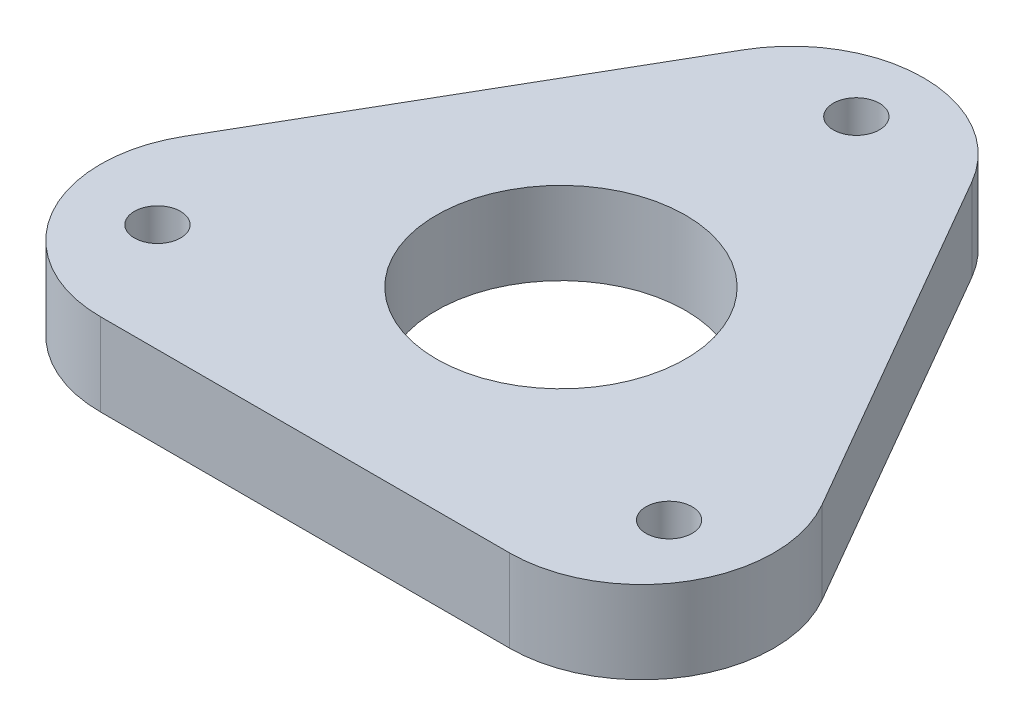
SolidWorks part; units mm, degrees
material "ASTM A36 Steel"
ref_plane "Front Plane" through (0, 0, 0) normal (0, 0, 1) x (1, 0, 0)
ref_plane "Top Plane" through (0, 0, 0) normal (0, 1, 0) x (1, 0, 0)
ref_plane "Right Plane" through (0, 0, 0) normal (1, 0, 0) x (0, 0, -1)
sketch "Sketch1" plane through (0, 0, 0) normal (0, 1, 0) x (1, 0, 0)
  line L0 (66.646, 85.1049) -> (128.644, -22.2787)
  line L1 (94.0029, -82.2787) -> (-29.993, -82.2787)
  line L2 (-64.634, -22.2787) -> (-2.636, 85.1049)
  arc A0 (66.646, 85.1049) -> (-2.636, 85.1049) centre (32.005, 65.1049) ccw
  arc A1 (-29.993, -82.2787) -> (-64.634, -22.2787) centre (-29.993, -42.2787) cw
  arc A2 (128.644, -22.2787) -> (94.0029, -82.2787) centre (94.0029, -42.2787) cw
  point P7 (-99.275, -82.2787)
  point P10 (163.285, -82.2787)
  dimension "D2" = 40
  dimension "D1" = 262.56
extrude "Boss-Extrude1" add sketch "Sketch1" along normal blind 25
sketch "Sketch2" plane through (0, 25, 0) normal (0, 1, 0) x (1, 0, 0)
  circle A0 centre (32.005, -4.7521) radius 37.75
  dimension "D1" = 75.5
extrude "Cut-Extrude1" cut sketch "Sketch2" against normal blind 28
sketch "Sketch3" plane through (0, 25, 0) normal (0, 1, 0) x (1, 0, 0)
  circle A0 centre (32.005, 84.7372) radius 7
  circle A1 centre (109.505, -49.4967) radius 7
  circle A2 centre (-45.495, -49.4967) radius 7
  dimension "D2" = 14
  dimension "D3" = 14
  dimension "D4" = 14
  dimension "D1" = 155
extrude "Cut-Extrude2" cut sketch "Sketch3" against normal through all
